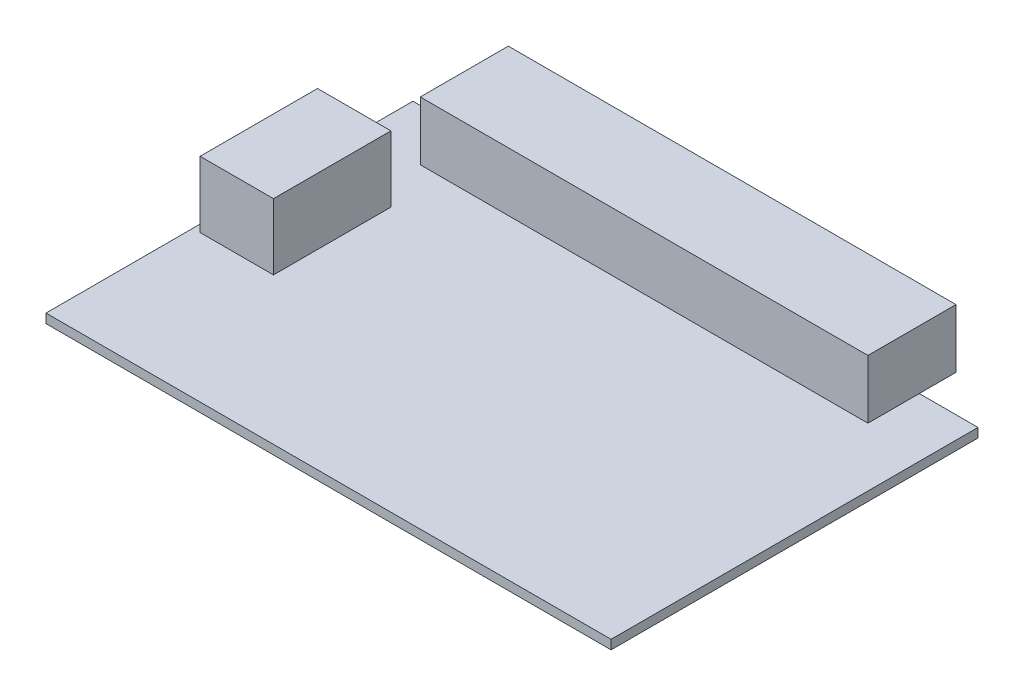
SolidWorks part; units mm, degrees
ref_plane "Front Plane" through (0, 0, 0) normal (0, 0, 1) x (1, 0, 0)
ref_plane "Top Plane" through (0, 0, 0) normal (0, 1, 0) x (1, 0, 0)
ref_plane "Right Plane" through (0, 0, 0) normal (1, 0, 0) x (0, 0, -1)
sketch "Sketch1" plane through (0, 0, 0) normal (0, 1, 0) x (1, 0, 0)
  line L1 (-38.5, -25) -> (38.5, -25)
  line L2 (-38.5, -25) -> (-38.5, 25)
  line L3 (-38.5, 25) -> (38.5, 25)
  line L4 (38.5, -25) -> (38.5, 25)
  line L5 (-38.5, -25) -> (38.5, 25) construction
  line L6 (-38.5, 25) -> (38.5, -25) construction
  point P0 (0, 0)
  dimension "D1" = 77
  dimension "D2" = 50
extrude "Boss-Extrude1" add sketch "Sketch1" along normal blind 1.25 contours L3 L4 L1 L2
sketch "Sketch2" plane through (0, 1.25, 0) normal (0, 1, 0) x (1, 0, 0)
  line L0 (-38.5, -25) -> (-38.5, 25) construction
  line L1 (-37.5, 11) -> (-27.5, 11)
  line L2 (-37.5, 11) -> (-37.5, -5)
  line L3 (-37.5, -5) -> (-27.5, -5)
  line L4 (-27.5, 11) -> (-27.5, -5)
  line L5 (-38.5, 25) -> (38.5, 25) construction
  dimension "D1" = 16
  dimension "D2" = 10
  dimension "D3" = 1
  dimension "D4" = 14
extrude "Boss-Extrude2" add sketch "Sketch2" along normal blind 9
sketch "Sketch3" plane through (0, 1.25, 0) normal (0, 1, 0) x (1, 0, 0)
  line L0 (-38.5, 25) -> (38.5, 25) construction
  line L1 (-30.5, 18) -> (30.5, 18)
  line L2 (-30.5, 18) -> (-30.5, 30)
  line L3 (-30.5, 30) -> (30.5, 30)
  line L4 (30.5, 18) -> (30.5, 30)
  line L5 (0, 30) -> (0, 18) construction
  line L6 (-38.5, -25) -> (-38.5, 25) construction
  line L7 (38.5, -25) -> (38.5, 25) construction
  dimension "D1" = 12
  dimension "D2" = 61
  dimension "D3" = 5
extrude "Boss-Extrude3" add sketch "Sketch3" along normal blind 8 contours L3 L4 L1 L2
